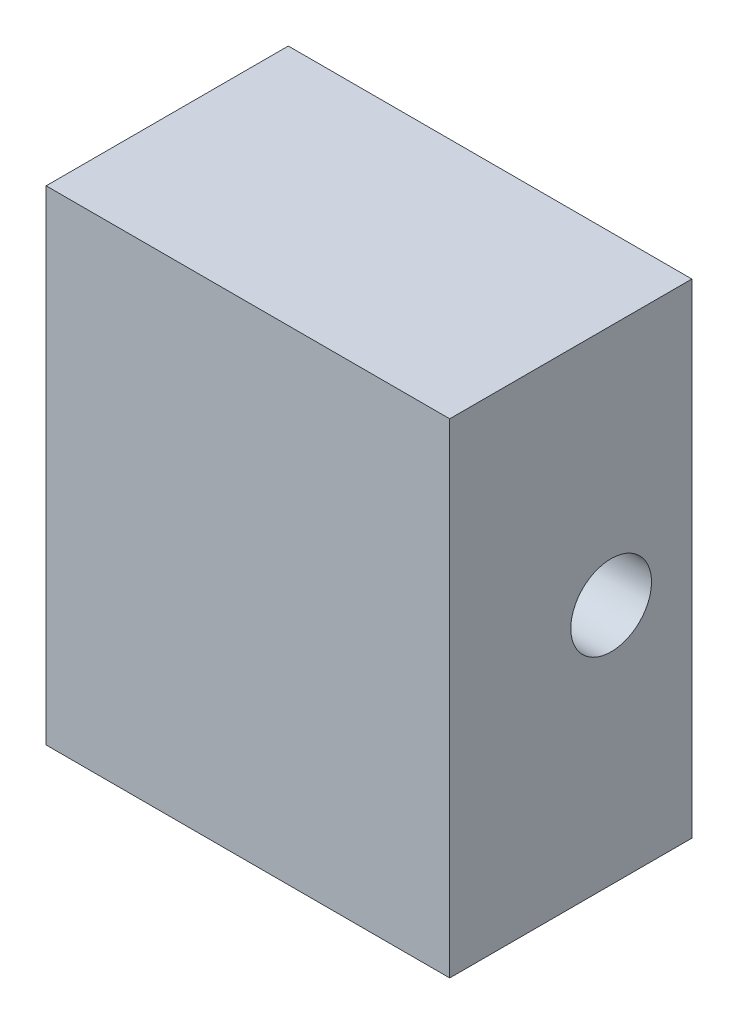
SolidWorks part; units mm, degrees
ref_plane "Front Plane" through (0, 0, 0) normal (0, 0, 1) x (1, 0, 0)
ref_plane "Top Plane" through (0, 0, 0) normal (0, 1, 0) x (1, 0, 0)
ref_plane "Right Plane" through (0, 0, 0) normal (1, 0, 0) x (0, 0, -1)
sketch "Sketch1" plane through (0, 0, 0) normal (0, 0, 1) x (1, 0, 0)
  line L1 (12.5, -15) -> (-12.5, -15)
  line L2 (12.5, -15) -> (12.5, 15)
  line L3 (12.5, 15) -> (-12.5, 15)
  line L4 (-12.5, -15) -> (-12.5, 15)
  line L5 (12.5, -15) -> (-12.5, 15) construction
  line L6 (12.5, 15) -> (-12.5, -15) construction
  point P0 (0, 0)
  dimension "D1" = 25
  dimension "D2" = 30
extrude "Boss-Extrude1" add sketch "Sketch1" along normal blind 15
sketch "Sketch2" plane through (-12.5, 0, 0) normal (-1, 0, 0) x (0, 0, 1)
  line L0 (15, 15) -> (15, -15) construction
  line L2 (15, 15) -> (0, 15) construction
  circle A0 centre (5, 0) radius 2.5
  dimension "D1" = 5
  dimension "D2" = 10
  dimension "D3" = 15
extrude "Cut-Extrude1" cut sketch "Sketch2" against normal blind 26
